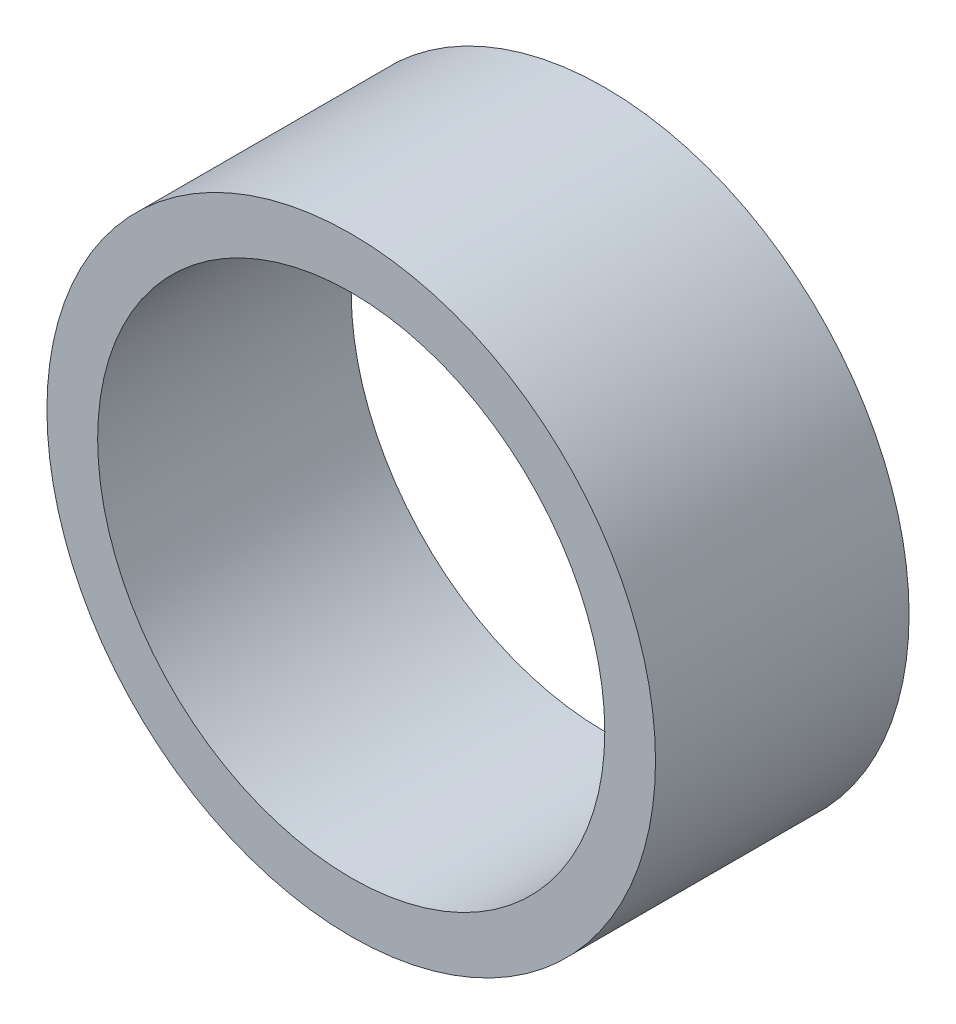
SolidWorks part; units mm, degrees
ref_plane "前视基准面" through (0, 0, 0) normal (0, 0, 1) x (1, 0, 0)
ref_plane "上视基准面" through (0, 0, 0) normal (0, 1, 0) x (1, 0, 0)
ref_plane "右视基准面" through (0, 0, 0) normal (1, 0, 0) x (0, 0, -1)
sketch "草图1" plane through (0, 0, 0) normal (0, 0, 1) x (1, 0, 0)
  circle A0 centre (0, 0) radius 6
  circle A1 centre (0, 0) radius 5
  dimension "D1" = 10
  dimension "D2" = 12
extrude "凸台-拉伸1" add sketch "草图1" along normal blind 5
